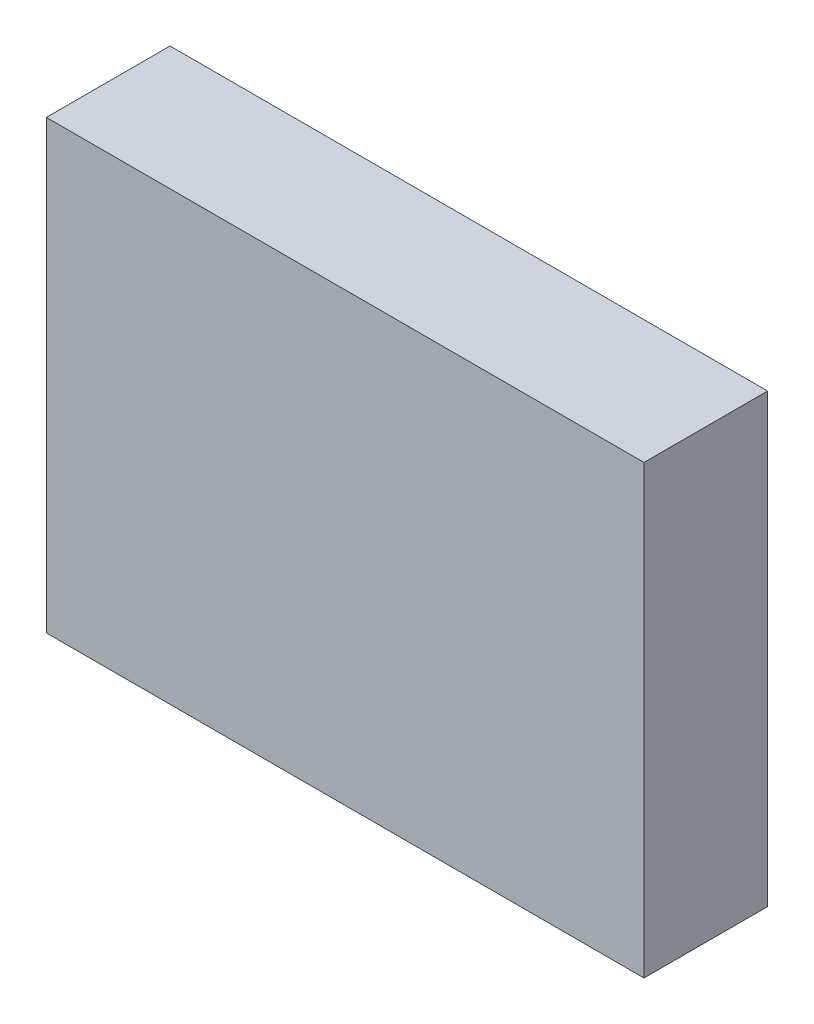
SolidWorks part; units mm, degrees
ref_plane "前视基准面" through (0, 0, 0) normal (0, 0, 1) x (1, 0, 0)
ref_plane "上视基准面" through (0, 0, 0) normal (0, 1, 0) x (1, 0, 0)
ref_plane "右视基准面" through (0, 0, 0) normal (1, 0, 0) x (0, 0, -1)
other "Configuration Table"
sketch "草图1" plane through (0, 0, 0) normal (0, 0, 1) x (1, 0, 0)
  line L1 (-43.5, 32.5) -> (43.5, 32.5)
  line L2 (-43.5, 32.5) -> (-43.5, -32.5)
  line L3 (-43.5, -32.5) -> (43.5, -32.5)
  line L4 (43.5, 32.5) -> (43.5, -32.5)
  line L5 (-43.5, 32.5) -> (43.5, -32.5) construction
  line L6 (-43.5, -32.5) -> (43.5, 32.5) construction
  point P0 (0, 0)
  dimension "D1" = 87
  dimension "D2" = 65
extrude "凸台-拉伸1" add sketch "草图1" along normal blind 18
